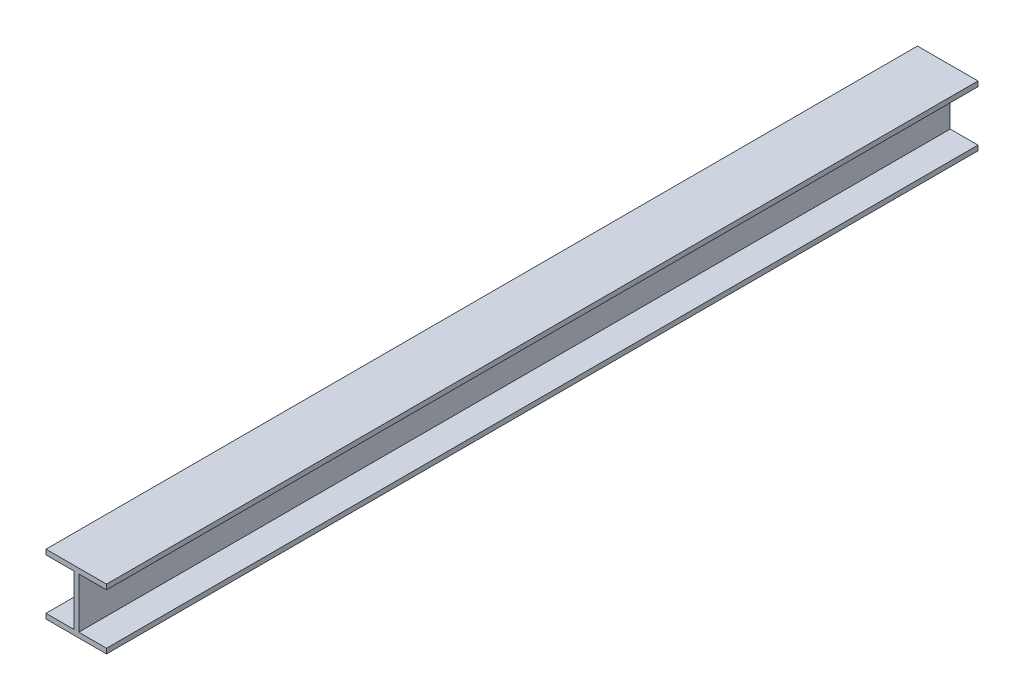
SolidWorks part; units mm, degrees
material "1060 Alloy"
ref_plane "Front Plane" through (0, 0, 0) normal (0, 0, 1) x (1, 0, 0)
ref_plane "Top Plane" through (0, 0, 0) normal (0, 1, 0) x (1, 0, 0)
ref_plane "Right Plane" through (0, 0, 0) normal (1, 0, 0) x (0, 0, -1)
sketch "Sketch1" plane through (0, 0, 0) normal (0, 0, 1) x (1, 0, 0)
  line L2 (-63.5, 63.5) -> (-63.5, 53.0352)
  line L3 (-63.5, 53.0352) -> (-5.2451, 53.0352)
  line L4 (-5.2451, 53.0352) -> (-5.2451, -53.0352)
  line L5 (-5.2451, -53.0352) -> (-63.5, -53.0352)
  line L6 (-63.5, -53.0352) -> (-63.5, -63.5)
  line L8 (-63.5, 63.5) -> (63.5, 63.5)
  line L9 (63.5, 63.5) -> (63.5, 53.0352)
  line L10 (63.5, 53.0352) -> (5.2451, 53.0352)
  line L11 (5.2451, 53.0352) -> (5.2451, -53.0352)
  line L12 (5.2451, -53.0352) -> (63.5, -53.0352)
  line L13 (63.5, -53.0352) -> (63.5, -63.5)
  line L14 (63.5, -63.5) -> (-63.5, -63.5)
  point P0 (0, 63.5)
  point P2 (5.2451, 0)
  dimension "D1" = 0
  dimension "D2" = 127
  dimension "D3" = 127
  dimension "D4" = 0
  dimension "D5" = 10.4902
  dimension "D6" = 10.4648
extrude "Boss-Extrude1" add sketch "Sketch1" along normal mid plane 1828.8
